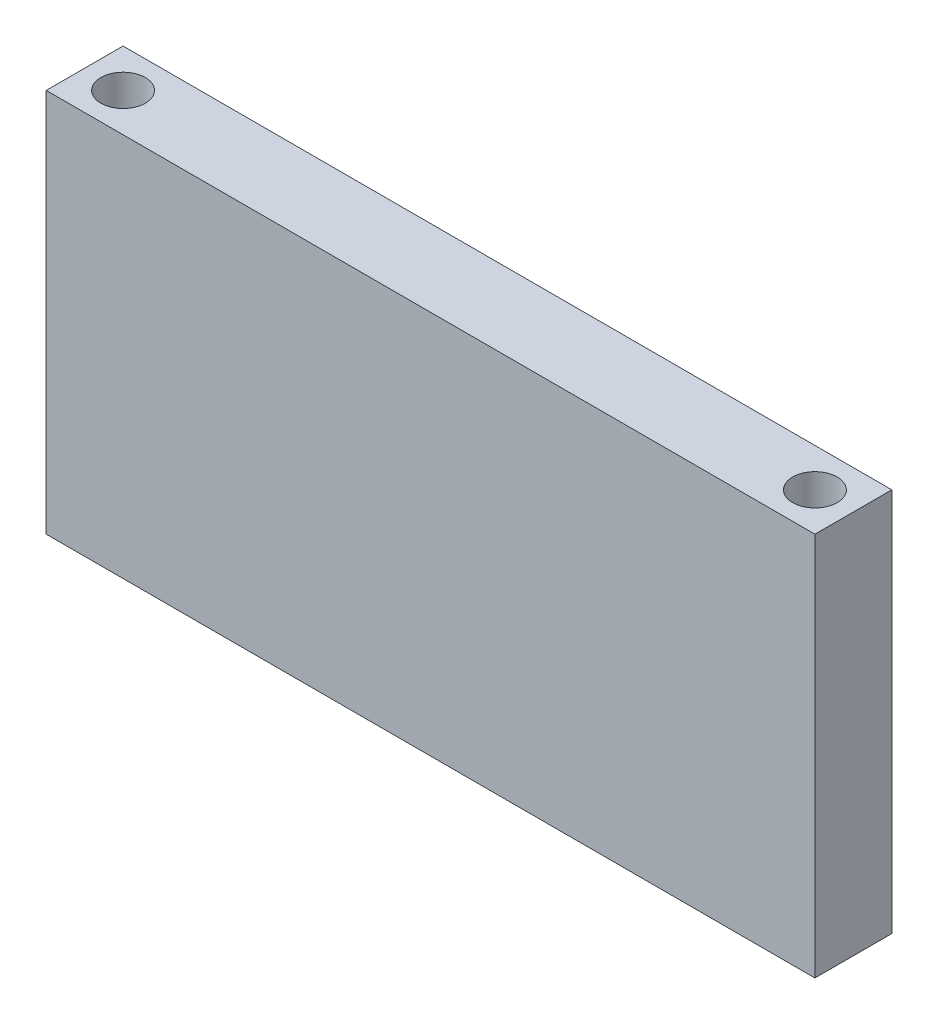
SolidWorks part; units mm, degrees
ref_plane "Front Plane" through (0, 0, 0) normal (0, 0, 1) x (1, 0, 0)
ref_plane "Top Plane" through (0, 0, 0) normal (0, 1, 0) x (1, 0, 0)
ref_plane "Right Plane" through (0, 0, 0) normal (1, 0, 0) x (0, 0, -1)
sketch "Sketch1" plane through (0, 0, 0) normal (0, 1, 0) x (1, 0, 0)
  line L1 (-38.7879, 10.7576) -> (61.2121, 10.7576)
  line L2 (-38.7879, 10.7576) -> (-38.7879, 0.7576)
  line L3 (-38.7879, 0.7576) -> (61.2121, 0.7576)
  line L4 (61.2121, 10.7576) -> (61.2121, 0.7576)
  dimension "D1" = 100
  dimension "D2" = 10
extrude "Boss-Extrude1" add sketch "Sketch1" along normal blind 50
hole_wizard "#1 (0.228) Diameter Hole1" positions "3DSketch1" profile "Sketch2" hole size "#1" standard "ANSI Inch" end condition through all
sketch3d "3DSketch1"
  line L0 (61.2121, 0, -0.7576) -> (61.2121, 0, -10.7576) construction
  line L1 (-38.7879, 0, -0.7576) -> (61.2121, 0, -0.7576) construction
  line L2 (-38.7879, 0, -10.7576) -> (-38.7879, 0, -0.7576) construction
  point P0 (56.2121, 0, -5.7576)
  point P2 (-33.7879, 0, -5.7576)
  dimension "D1" = 5
  dimension "D2" = 5
  dimension "D3" = 5
  dimension "D4" = 5
sketch "Sketch2" plane through (56.2121, 0, -5.7576) normal (1, 0, 0) x (0, 0, -1)
  line L0 (0, 0) -> (0, 50)
  line L1 (0, 50) -> (2.8956, 50)
  line L2 (2.8956, 50) -> (2.8956, 0)
  line L5 (2.8956, 0) -> (0, 0)
  line L11 (0, -6.35) -> (0, 107.95) construction
  dimension "Thru Hole Dia." = 5.7912
  dimension "Thru Hole Depth" = 50
